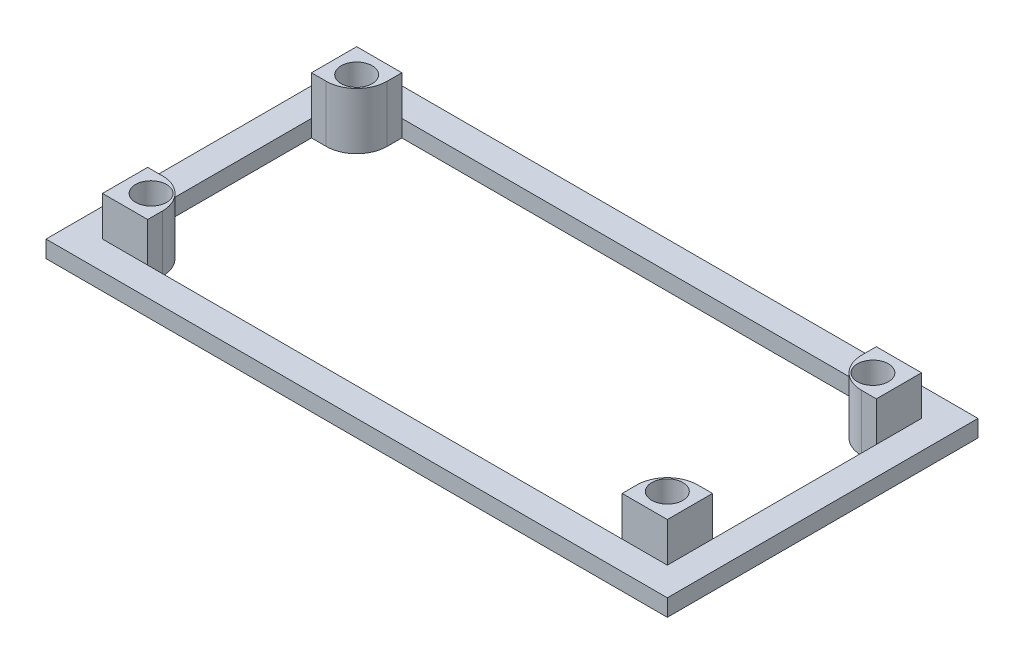
SolidWorks part; units mm, degrees
ref_plane "Front Plane" through (0, 0, 0) normal (0, 0, 1) x (1, 0, 0)
ref_plane "Top Plane" through (0, 0, 0) normal (0, 1, 0) x (1, 0, 0)
ref_plane "Right Plane" through (0, 0, 0) normal (1, 0, 0) x (0, 0, -1)
sketch "Sketch1" plane through (0, 0, 0) normal (0, 1, 0) x (1, 0, 0)
  line L1 (55, 27.5) -> (-55, 27.5)
  line L2 (55, 27.5) -> (55, -27.5)
  line L3 (55, -27.5) -> (-55, -27.5)
  line L4 (-55, 27.5) -> (-55, -27.5)
  line L5 (55, 27.5) -> (-55, -27.5) construction
  line L6 (55, -27.5) -> (-55, 27.5) construction
  line L7 (-50, -22.5) -> (50, -22.5)
  line L8 (-50, -22.5) -> (-50, 22.5)
  line L9 (-50, 22.5) -> (50, 22.5)
  line L10 (50, -22.5) -> (50, 22.5)
  line L11 (-50, -22.5) -> (50, 22.5) construction
  line L12 (-50, 22.5) -> (50, -22.5) construction
  point P0 (0, 0)
  point P6 (0, 0)
  dimension "D1" = 110
  dimension "D2" = 55
  dimension "D3" = 100
  dimension "D4" = 45
extrude "Boss-Extrude1" add sketch "Sketch1" along normal blind 3
sketch "Sketch2" plane through (0, 3, 0) normal (0, 1, 0) x (1, 0, 0)
  line L0 (-50, -22.5) -> (-42, -22.5)
  line L1 (-50, -22.5) -> (50, -22.5) construction
  line L2 (-50, 22.5) -> (-50, -22.5) construction
  line L3 (-50, -14.5) -> (-50, -22.5)
  line L4 (-42, -22.5) -> (-42, -19.8899)
  line L5 (-47.3899, -14.5) -> (-50, -14.5)
  circle A1 centre (-45.7, -18.2) radius 2.75
  arc A2 (-42, -19.8899) -> (-47.3899, -14.5) centre (-47.3899, -19.8899) ccw
  point P13 (-43.5787, -16.0787)
  dimension "D1" = 3
  dimension "D2" = 5.5
  dimension "D3" = 4.3
  dimension "D4" = 4.3
  dimension "D5" = 8
extrude "Boss-Extrude2" add sketch "Sketch2" along normal blind 7 and the other way up to surface
mirror "Mirror1" about plane through (0, 0, 0) normal (0, 0, 1) of "Boss-Extrude2" second plane through (0, 0, 0) second plane normal (1, 0, 0)
